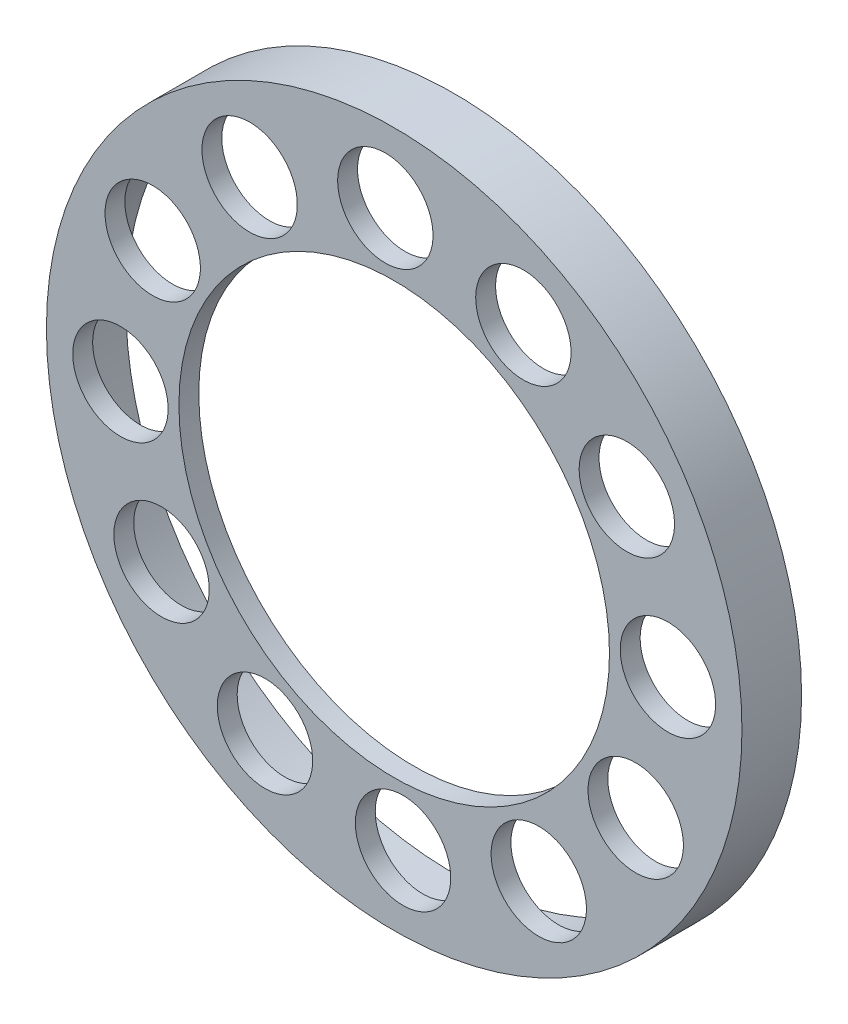
SolidWorks part; units mm, degrees
ref_plane "Front Plane" through (0, 0, 0) normal (0, 0, 1) x (1, 0, 0)
ref_plane "Top Plane" through (0, 0, 0) normal (0, 1, 0) x (1, 0, 0)
ref_plane "Right Plane" through (0, 0, 0) normal (1, 0, 0) x (0, 0, -1)
sketch "Sketch1" plane through (0, 0, 0) normal (0, 0, 1) x (1, 0, 0)
  line L0 (0, 13.335) -> (0, 8.255) construction
  circle A0 centre (0, 0) radius 13.335
  circle A1 centre (0, 0) radius 8.255
  circle A2 centre (8.92, 5.5426) radius 1.5748 construction
  circle A3 centre (8.92, 5.5426) radius 1.8288
  circle A4 centre (10.4962, 0.34) radius 1.8288
  circle A5 centre (9.26, -4.9536) radius 1.8288
  circle A6 centre (5.5426, -8.92) radius 1.8288
  circle A7 centre (0.34, -10.4962) radius 1.8288
  circle A8 centre (-4.9536, -9.26) radius 1.8288
  circle A9 centre (-8.92, -5.5426) radius 1.8288
  circle A10 centre (-10.4962, -0.34) radius 1.8288
  circle A11 centre (-9.26, 4.9536) radius 1.8288
  circle A12 centre (-5.5426, 8.92) radius 1.8288
  circle A13 centre (-0.34, 10.4962) radius 1.8288
  circle A14 centre (4.9536, 9.26) radius 1.8288
  point P35 (0, 0)
  dimension "D1" = 16.51
  dimension "D2" = 5.08
  dimension "D3" = 0.254
  dimension "D4" = 12
extrude "Boss-Extrude1" add sketch "Sketch1" along normal blind 0.762
sketch "Sketch2" plane through (0, 0, 0) normal (0, 0, -1) x (-1, 0, 0)
  circle A0 centre (0, 0) radius 13.335
  circle A1 centre (0, 0) radius 12.573
  dimension "D1" = 0.762
extrude "Boss-Extrude2" add sketch "Sketch2" along normal blind 1.524
